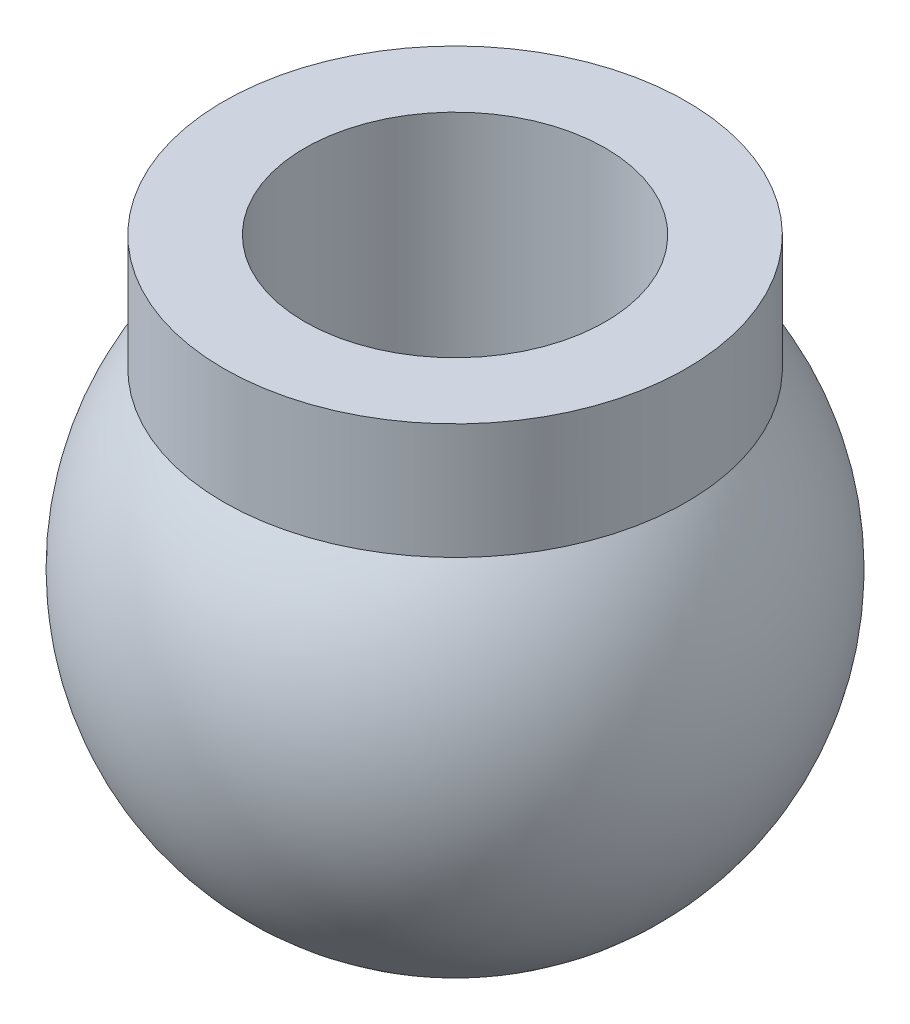
SolidWorks part; units mm, degrees
ref_plane "Front Plane" through (0, 0, 0) normal (0, 0, 1) x (1, 0, 0)
ref_plane "Top Plane" through (0, 0, 0) normal (0, 1, 0) x (1, 0, 0)
ref_plane "Right Plane" through (0, 0, 0) normal (1, 0, 0) x (0, 0, -1)
sketch "Sketch1" plane through (0, 0, 0) normal (0, 0, 1) x (1, 0, 0)
  line L2 (4.6643, 0) -> (-6.7323, 0) construction
  line L3 (-2.5, 0) -> (2.5, 0)
  arc A0 (-2.5, 0) -> (2.5, 0) centre (0, 0) ccw
  dimension "D1" = 5
revolve "Revolve2" add sketch "Sketch1" angle 360 about L2
sketch "Sketch2" plane through (0, 0, 0) normal (0, 1, 0) x (1, 0, 0)
  circle A0 centre (0, 0) radius 1.3
  dimension "D1" = 2.6
extrude "Cut-Extrude1" cut sketch "Sketch2" against normal mid plane 30
sketch "Sketch3" plane through (0, 0, 0) normal (0, 1, 0) x (1, 0, 0)
  circle A0 centre (0, 0) radius 2
  circle A1 centre (0, 0) radius 1.3
  dimension "D1" = 2.6
  dimension "D2" = 4
extrude "Boss-Extrude1" add sketch "Sketch3" along normal blind 2.5
